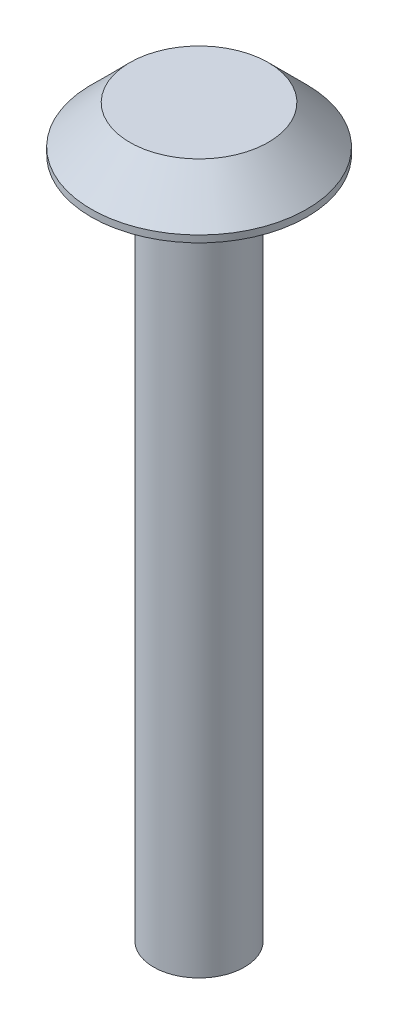
SolidWorks part; units mm, degrees
ref_plane "Front Plane" through (0, 0, 0) normal (0, 0, 1) x (1, 0, 0)
ref_plane "Top Plane" through (0, 0, 0) normal (0, 1, 0) x (1, 0, 0)
ref_plane "Right Plane" through (0, 0, 0) normal (1, 0, 0) x (0, 0, -1)
sketch "Sketch1" plane through (0, 0, 0) normal (0, 1, 0) x (1, 0, 0)
  circle A0 centre (0, 0) radius 2
  dimension "D1" = 4
extrude "Boss-Extrude1" add sketch "Sketch1" along normal blind 30
sketch "Sketch2" plane through (0, 30, 0) normal (0, 1, 0) x (1, 0, 0)
  circle A0 centre (0, 0) radius 4.75
  dimension "D1" = 9.5
extrude "Boss-Extrude2" add sketch "Sketch2" along normal blind 2 contours A0
chamfer "Chamfer1" distance 1.7 angle 45 1 edges at (0, 32, 4.75)
